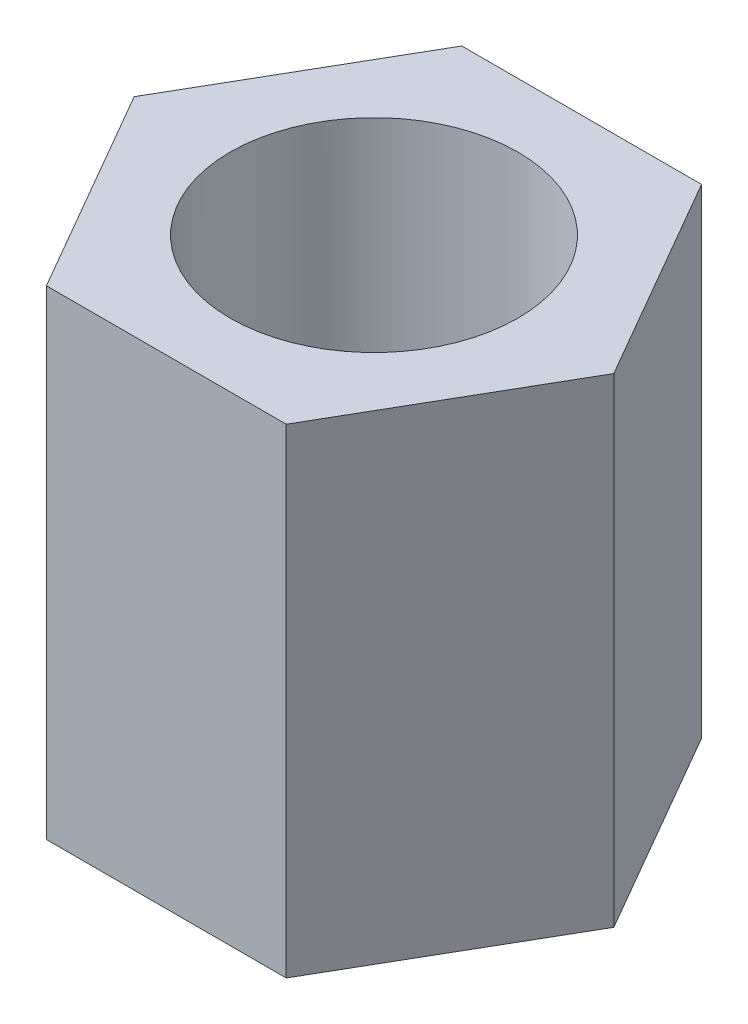
SolidWorks part; units mm, degrees
material "2.0402 (CuZn40Pb2)"
ref_plane "Front" through (0, 0, 0) normal (0, 0, 1) x (1, 0, 0)
ref_plane "Top" through (0, 0, 0) normal (0, 1, 0) x (1, 0, 0)
ref_plane "Right" through (0, 0, 0) normal (1, 0, 0) x (0, 0, -1)
sketch "Эскиз1" plane through (0, 0, 0) normal (0, 1, 0) x (1, 0, 0)
  line L1 (1.25, -2.1651) -> (2.5, 0)
  line L2 (2.5, 0) -> (1.25, 2.1651)
  line L3 (1.25, 2.1651) -> (-1.25, 2.1651)
  line L4 (-1.25, 2.1651) -> (-2.5, 0)
  line L5 (-2.5, 0) -> (-1.25, -2.1651)
  line L6 (-1.25, -2.1651) -> (1.25, -2.1651)
  circle A0 centre (0, 0) radius 2.1651 construction
  circle A1 centre (0, 0) radius 2.5 construction
  dimension "D1" = 5
  dimension "D2" = 2.5
extrude "Бобышка-Вытянуть1" add sketch "Эскиз1" along normal blind 5
sketch "Эскиз2" plane through (0, 5, 0) normal (0, 1, 0) x (1, 0, 0)
  circle A0 centre (0, 0) radius 1.5
  dimension "D1" = 3
extrude "Бобышка-Вытянуть2" add sketch "Эскиз2" along normal blind 5
sketch "Эскиз3" plane through (0, 0, 0) normal (0, -1, 0) x (1, 0, 0)
  circle A0 centre (0, 0) radius 1.5
  dimension "D1" = 3
extrude "Вырез-Вытянуть1" cut sketch "Эскиз3" against normal blind 10
